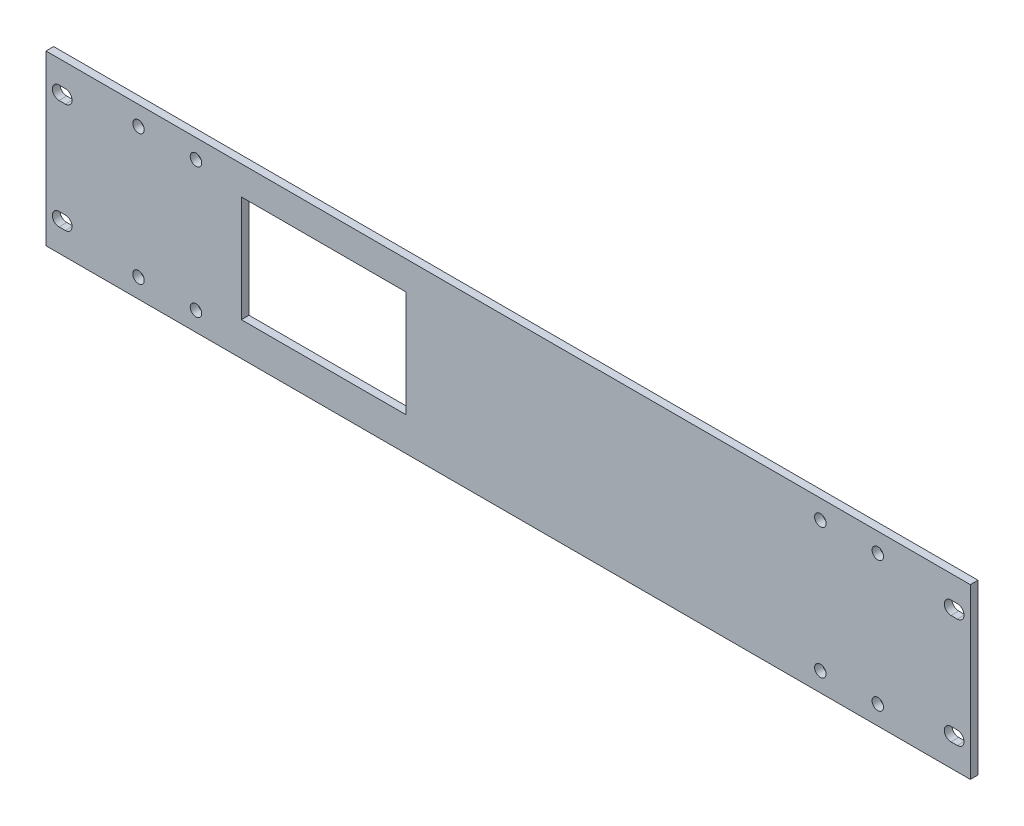
SolidWorks part; units mm, degrees
material "1060 Сплав"
ref_plane "Front" through (0, 0, 0) normal (0, 0, 1) x (1, 0, 0)
ref_plane "Top" through (0, 0, 0) normal (0, 1, 0) x (1, 0, 0)
ref_plane "Right" through (0, 0, 0) normal (1, 0, 0) x (0, 0, -1)
sketch "Эскиз1" plane through (0, 0, 0) normal (0, 0, 1) x (1, 0, 0)
  line L1 (0, 0) -> (482.6, 0)
  line L2 (0, 0) -> (0, 88.1)
  line L3 (0, 88.1) -> (482.6, 88.1)
  line L4 (482.6, 0) -> (482.6, 88.1)
  dimension "D1" = 88.1
  dimension "D2" = 482.6
extrude "Бобышка-Вытянуть1" add sketch "Эскиз1" along normal blind 4
sketch "Эскиз2" plane through (0, 0, 4) normal (0, 0, 1) x (1, 0, 0)
  line L0 (6.8, 72.62) -> (10.1, 72.62) construction
  line L1 (6.8, 76.12) -> (10.1, 76.12)
  line L2 (6.8, 69.12) -> (10.1, 69.12)
  line L3 (0, 88.1) -> (0, 0) construction
  line L4 (482.6, 88.1) -> (0, 88.1) construction
  line L5 (472.5, 72.62) -> (475.8, 72.62) construction
  line L6 (472.5, 76.12) -> (475.8, 76.12)
  line L7 (472.5, 69.12) -> (475.8, 69.12)
  line L8 (472.5, 15.47) -> (475.8, 15.47) construction
  line L9 (472.5, 18.97) -> (475.8, 18.97)
  line L10 (472.5, 11.97) -> (475.8, 11.97)
  line L11 (6.8, 15.47) -> (10.1, 15.47) construction
  line L12 (6.8, 18.97) -> (10.1, 18.97)
  line L13 (6.8, 11.97) -> (10.1, 11.97)
  line L15 (482.6, 0) -> (482.6, 88.1) construction
  arc A0 (6.8, 76.12) -> (6.8, 69.12) centre (6.8, 72.62) ccw
  arc A1 (10.1, 69.12) -> (10.1, 76.12) centre (10.1, 72.62) ccw
  arc A2 (472.5, 76.12) -> (472.5, 69.12) centre (472.5, 72.62) ccw
  arc A3 (475.8, 69.12) -> (475.8, 76.12) centre (475.8, 72.62) ccw
  arc A4 (472.5, 18.97) -> (472.5, 11.97) centre (472.5, 15.47) ccw
  arc A5 (475.8, 11.97) -> (475.8, 18.97) centre (475.8, 15.47) ccw
  arc A6 (6.8, 18.97) -> (6.8, 11.97) centre (6.8, 15.47) ccw
  arc A7 (10.1, 11.97) -> (10.1, 18.97) centre (10.1, 15.47) ccw
  point P2 (8.45, 72.62)
  point P16 (474.15, 72.62)
  point P23 (474.15, 15.47)
  point P30 (8.45, 15.47)
  dimension "D2" = 3.5
  dimension "D4" = 15.48
  dimension "D7" = 6.8
  dimension "D1" = 3.3
  dimension "D3" = 6.8
  dimension "D5" = 2
  dimension "D6" = 2
extrude "Вырез-Вытянуть1" cut sketch "Эскиз2" against normal through all
sketch "Эскиз3" plane through (0, 0, 4) normal (0, 0, 1) x (1, 0, 0)
  line L0 (0, 88.1) -> (0, 0) construction
  line L1 (482.6, 88.1) -> (0, 88.1) construction
  line L2 (0, 0) -> (482.6, 0) construction
  line L3 (482.6, 0) -> (482.6, 88.1) construction
  circle A0 centre (78.3, 78.1) radius 3
  circle A1 centre (404.3, 78.1) radius 3
  circle A2 centre (404.3, 10) radius 3
  circle A3 centre (78.3, 10) radius 3
  circle A4 centre (48.3, 78.1) radius 3
  circle A5 centre (434.3, 78.1) radius 3
  circle A6 centre (434.3, 10) radius 3
  circle A7 centre (48.3, 10) radius 3
  dimension "D1" = 6
  dimension "D2" = 78.3
  dimension "D3" = 10
  dimension "D6" = 10
  dimension "D7" = 78.3
  dimension "D8" = 6
  dimension "D9" = 30
  dimension "D10" = 10
  dimension "D13" = 30
  dimension "D14" = 10
  dimension "D15" = 10
  dimension "D4" = 2
  dimension "D5" = 2
  dimension "D11" = 2
  dimension "D12" = 2
extrude "Вырез-Вытянуть2" cut sketch "Эскиз3" against normal through all
sketch "Эскиз4" plane through (0, 0, 4) normal (0, 0, 1) x (1, 0, 0)
  line L0 (0, 88.1) -> (0, 0) construction
  line L1 (102, 73.1) -> (188, 73.1)
  line L2 (102, 73.1) -> (102, 17.6)
  line L3 (102, 17.6) -> (188, 17.6)
  line L4 (188, 73.1) -> (188, 17.6)
  line L5 (482.6, 88.1) -> (0, 88.1) construction
  dimension "D1" = 55.5
  dimension "D2" = 86
  dimension "D3" = 102
  dimension "D4" = 15
extrude "Вырез-Вытянуть3" cut sketch "Эскиз4" against normal through all
